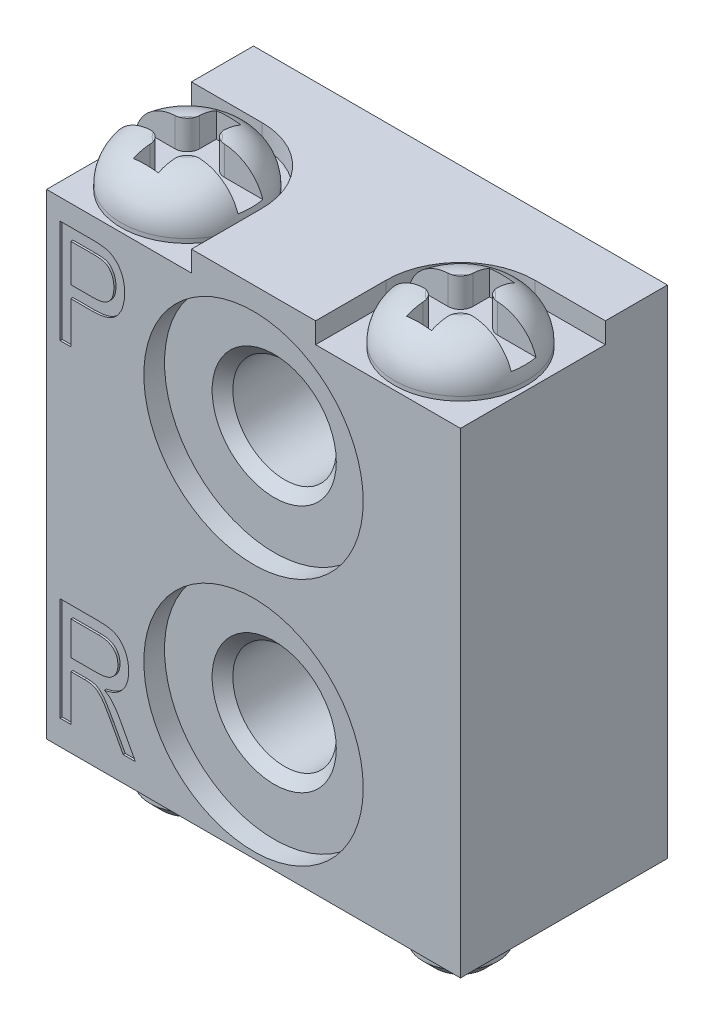
SolidWorks part; units mm, degrees
ref_plane "Front Plane" through (0, 0, 0) normal (0, 0, 1) x (1, 0, 0)
ref_plane "Top Plane" through (0, 0, 0) normal (0, 1, 0) x (1, 0, 0)
ref_plane "Right Plane" through (0, 0, 0) normal (1, 0, 0) x (0, 0, -1)
sketch "Sketch1" plane through (0, 0, 0) normal (0, 0, 1) x (1, 0, 0)
  line L1 (-5, 6) -> (5, 6)
  line L2 (-5, 6) -> (-5, -6)
  line L3 (-5, -6) -> (5, -6)
  line L4 (5, 6) -> (5, -6)
  line L5 (-5, 6) -> (5, -6) construction
  line L6 (-5, -6) -> (5, 6) construction
  point P0 (0, 0)
  dimension "D1" = 10
  dimension "D2" = 12
extrude "Boss-Extrude1" add sketch "Sketch1" along normal mid plane 5
sketch "Sketch2" plane through (0, 6, 0) normal (0, 1, 0) x (1, 0, 0)
  line L1 (-5, -2.5) -> (-1.5, -2.5)
  line L2 (-5, -2.5) -> (-5, 1)
  line L3 (-5, 1) -> (-3.3, 1)
  line L4 (-1.5, -2.5) -> (-1.5, -0.8)
  line L5 (5, -2.5) -> (1.5, -2.5)
  line L6 (5, -2.5) -> (5, 1)
  line L7 (5, 1) -> (3.3, 1)
  line L8 (1.5, -2.5) -> (1.5, -0.8)
  arc A0 (3.3, 1) -> (1.5, -0.8) centre (3.3, -0.8) ccw
  arc A1 (-3.3, 1) -> (-1.5, -0.8) centre (-3.3, -0.8) cw
  dimension "D2" = 1.8
  dimension "D1" = 3.5
extrude "Cut-Extrude1" cut sketch "Sketch2" against normal blind 0.5
sketch "Sketch3" plane through (0, 5.5, 0) normal (0, 1, 0) x (1, 0, 0)
  circle A0 centre (-3.3, -0.8) radius 1.6
  circle A1 centre (3.3, -0.8) radius 1.6
  dimension "D1" = 3.2
extrude "Boss-Extrude2" add sketch "Sketch3" along normal blind 1.1
fillet "Fillet1" radius 1 2 edges at (3.3, 6.6, 2.4) (-3.3, 6.6, 2.4)
sketch "Sketch4" plane through (0, 6.6, 0) normal (0, 1, 0) x (1, 0, 0)
  line L0 (-2.7, -0.5) -> (-1.7, -0.5)
  line L1 (-3.6, 0.2) -> (-3, 0.2)
  line L2 (-3.6, 0.2) -> (-3.6, -0.2)
  line L3 (-3.6, -1.8) -> (-3, -1.8)
  line L4 (-3, 0.2) -> (-3, -0.2)
  line L5 (-4.9, -0.5) -> (-3.9, -0.5)
  line L6 (-4.9, -0.5) -> (-4.9, -1.1)
  line L7 (-4.9, -1.1) -> (-3.9, -1.1)
  line L8 (-1.7, -0.5) -> (-1.7, -1.1)
  line L9 (-3.6, -1.4) -> (-3.6, -1.8)
  line L10 (-3, -1.4) -> (-3, -1.8)
  line L11 (-2.7, -1.1) -> (-1.7, -1.1)
  line L12 (3, -1.4) -> (3, -1.8)
  line L13 (3, 0.2) -> (3.6, 0.2)
  line L14 (3, -1.8) -> (3.6, -1.8)
  line L15 (3.6, 0.2) -> (3.6, -0.2)
  line L16 (3, 0.2) -> (3, -0.2)
  line L17 (4.9, -0.5) -> (4.9, -1.1)
  line L18 (1.7, -0.5) -> (1.7, -1.1)
  line L19 (3.9, -1.1) -> (4.9, -1.1)
  line L20 (3.6, -1.4) -> (3.6, -1.8)
  line L21 (3.9, -0.5) -> (4.9, -0.5)
  line L22 (1.7, -0.5) -> (2.7, -0.5)
  line L23 (1.7, -1.1) -> (2.7, -1.1)
  circle A0 centre (-3.3, -0.8) radius 0.6 construction
  circle A1 centre (-3.3, -0.8) radius 1.6 construction
  arc A2 (-3.6, -1.4) -> (-3.9, -1.1) centre (-3.9, -1.4) ccw
  arc A3 (-3, -1.4) -> (-2.7, -1.1) centre (-2.7, -1.4) cw
  arc A4 (-2.7, -0.5) -> (-3, -0.2) centre (-2.7, -0.2) cw
  arc A5 (-3.9, -0.5) -> (-3.6, -0.2) centre (-3.9, -0.2) ccw
  arc A6 (3.9, -0.5) -> (3.6, -0.2) centre (3.9, -0.2) cw
  arc A7 (3, -1.4) -> (2.7, -1.1) centre (2.7, -1.4) ccw
  arc A8 (3.6, -1.4) -> (3.9, -1.1) centre (3.9, -1.4) cw
  arc A9 (2.7, -0.5) -> (3, -0.2) centre (2.7, -0.2) ccw
  circle A10 centre (3.3, -0.8) radius 1.6 construction
  circle A11 centre (3.3, -0.8) radius 0.6 construction
  point P20 (-3, -1.1)
  dimension "D6" = 0.3
  dimension "D10" = 0.3
  dimension "D12" = 0.3
  dimension "D1" = 0.6
  dimension "D2" = 2
  dimension "D3" = 0.7
  dimension "D4" = 0.3
  dimension "D5" = 0.3
  dimension "D7" = 0.6
  dimension "D8" = 2
  dimension "D9" = 0.7
  dimension "D11" = 0.3
extrude "Cut-Extrude2" cut sketch "Sketch4" against normal blind 0.7
sketch "Sketch5" plane through (0, -6, 0) normal (0, -1, 0) x (1, 0, 0)
  circle A0 centre (-3.3, 0.8) radius 0.9
  circle A1 centre (3.3, 0.8) radius 0.9
  dimension "D1" = 1.8
extrude "Boss-Extrude3" add sketch "Sketch5" along normal blind 1.2
chamfer "Chamfer1" distance 0.3 angle 45 2 edges at (3.3, -7.2, -0.1) (-3.3, -7.2, -0.1)
sketch "Sketch6" plane through (0, 0, 2.5) normal (0, 0, 1) x (1, 0, 0)
  line L0 (-5, -6) -> (5, -6) construction
  circle A0 centre (0, 2.8) radius 2.65
  circle A1 centre (0, -3.2) radius 2.65
  dimension "D2" = 6
  dimension "D3" = 5.3
  dimension "D1" = 2.8
extrude "Cut-Extrude3" cut sketch "Sketch6" against normal blind 0.5
hole_wizard "Tap Drill for M3x0.5 Tap1" positions "Sketch8" profile "Sketch7" hole size "M3x0.5" standard "ANSI Metric"
sketch "Sketch8" plane through (0, 0, 2) normal (0, 0, 1) x (1, 0, 0)
  point P0 (0, 2.8)
  point P3 (0, -3.2)
sketch "Sketch7" plane through (0, 2.8, 2) normal (1, 0, 0) x (0, -1, 0)
  line L0 (0, 0) -> (0, 3.7511)
  line L1 (0, 3.7511) -> (1.25, 3)
  line L2 (1.25, 3) -> (1.25, 0.25)
  line L3 (1.25, 0.25) -> (1.5, 0)
  line L5 (1.5, 0) -> (0, 0)
  line L6 (-1.25, 0.25) -> (-1.5, 0) construction
  line L10 (0, 3.7511) -> (-1.25, 3) construction
  line L11 (0, -6.35) -> (0, 107.95) construction
  dimension "Hole Dia." = 2.5
  dimension "Hole Depth" = 3
  dimension "Near C'Sink Dia." = 3
  dimension "Near C'Sink Angle" = 90
  dimension "Drill Angle" = 118
sketch "Sketch9" plane through (0, 0, 2.5) normal (0, 0, 1) x (1, 0, 0)
  line L0 (-5, 5.5) -> (-5, -6) construction
  line L1 (-5, 5.5) -> (-1.5, 5.5) construction
  line L2 (-5, -6) -> (5, -6) construction
  text T0 "P" font "Arial Narrow" height 2.5
  text T1 "R" font "Arial Narrow" height 2.5
  dimension "D1" = 0.1
  dimension "D2" = 3
  dimension "D3" = 0.6
extrude "Cut-Extrude4" cut sketch "Sketch9" against normal blind 0.05
sketch "Sketch10" plane through (0, 0, -2.5) normal (0, 0, -1) x (-1, 0, 0)
  line L0 (-3.3, -0.5) -> (3.3, -0.5) construction
  line L1 (5, -6) -> (-5, -6) construction
  line L2 (0, 0) -> (0, -0.5) construction
  circle A0 centre (-3.3, -0.5) radius 0.85
  circle A1 centre (3.3, -0.5) radius 0.85
  dimension "D3" = 1.7
  dimension "D1" = 6.6
  dimension "D2" = 5.5
extrude "Cut-Extrude5" cut sketch "Sketch10" against normal blind 1.5
